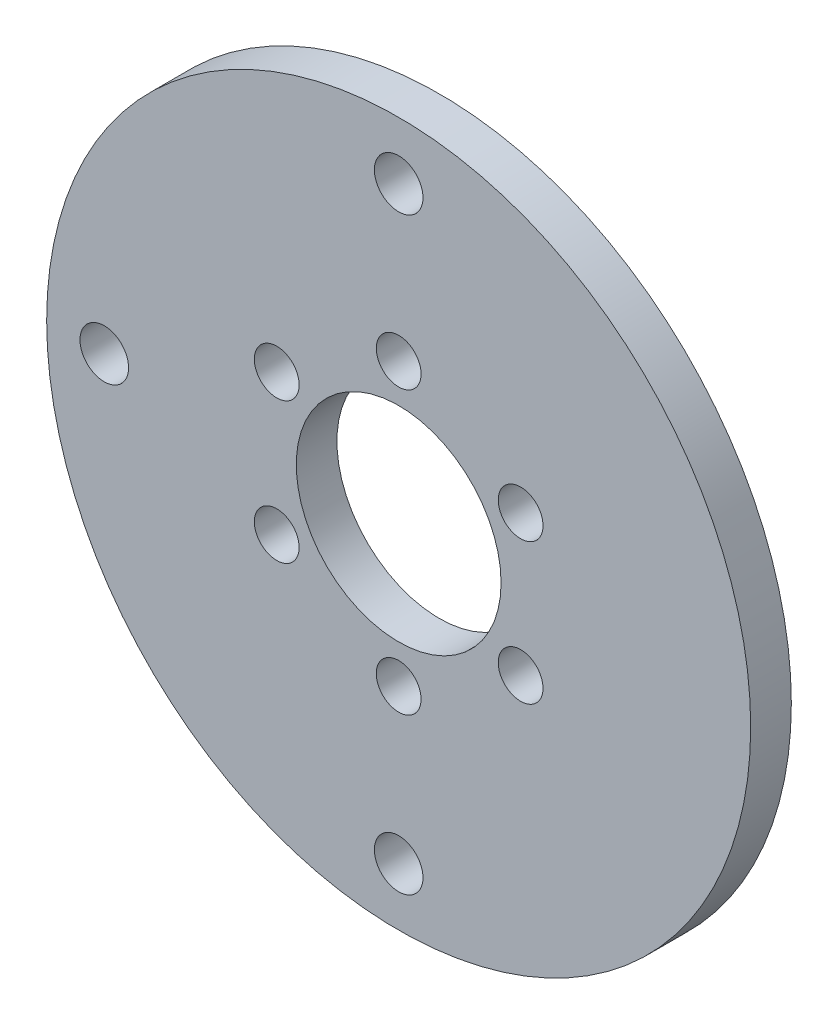
SolidWorks part; units mm, degrees
material "Balsa"
ref_plane "Front Plane" through (0, 0, 0) normal (0, 0, 1) x (1, 0, 0)
ref_plane "Top Plane" through (0, 0, 0) normal (0, 1, 0) x (1, 0, 0)
ref_plane "Right Plane" through (0, 0, 0) normal (1, 0, 0) x (0, 0, -1)
sketch "Sketch1" plane through (0, 0, 0) normal (0, 0, 1) x (1, 0, 0)
  circle A0 centre (0, 0) radius 27.5
  circle A1 centre (0, 0) radius 8
  circle A2 centre (0, 0) radius 23 construction
  circle A3 centre (0, 23) radius 1.8986
  circle A4 centre (16.2635, 16.2635) radius 1.5 construction
  circle A5 centre (23, 0) radius 1.8986 construction
  circle A6 centre (16.2635, -16.2635) radius 1.5 construction
  circle A7 centre (0, -23) radius 1.8986
  circle A8 centre (-16.2635, -16.2635) radius 1.5 construction
  circle A9 centre (-23, 0) radius 1.8986
  circle A10 centre (-16.2635, 16.2635) radius 1.5 construction
  circle A11 centre (0, 0) radius 11 construction
  circle A12 centre (0, 11) radius 1.75
  circle A13 centre (9.5263, 5.5) radius 1.75
  circle A14 centre (9.5263, -5.5) radius 1.75
  circle A15 centre (0, -11) radius 1.75
  circle A16 centre (-9.5263, -5.5) radius 1.75
  circle A17 centre (-9.5263, 5.5) radius 1.75
  dimension "D1" = 55
  dimension "D2" = 16
  dimension "D4" = 46
  dimension "D5" = 3.7973
  dimension "D6" = 3
  dimension "D8" = 3.5
  dimension "D10" = 22
  dimension "D3" = 45
  dimension "D9" = 60
  dimension "D7" = 4
  dimension "D11" = 3
extrude "Boss-Extrude1" add sketch "Sketch1" along normal blind 3.175
other "Move Face1" [suppressed] parameters "D1"=0.08
